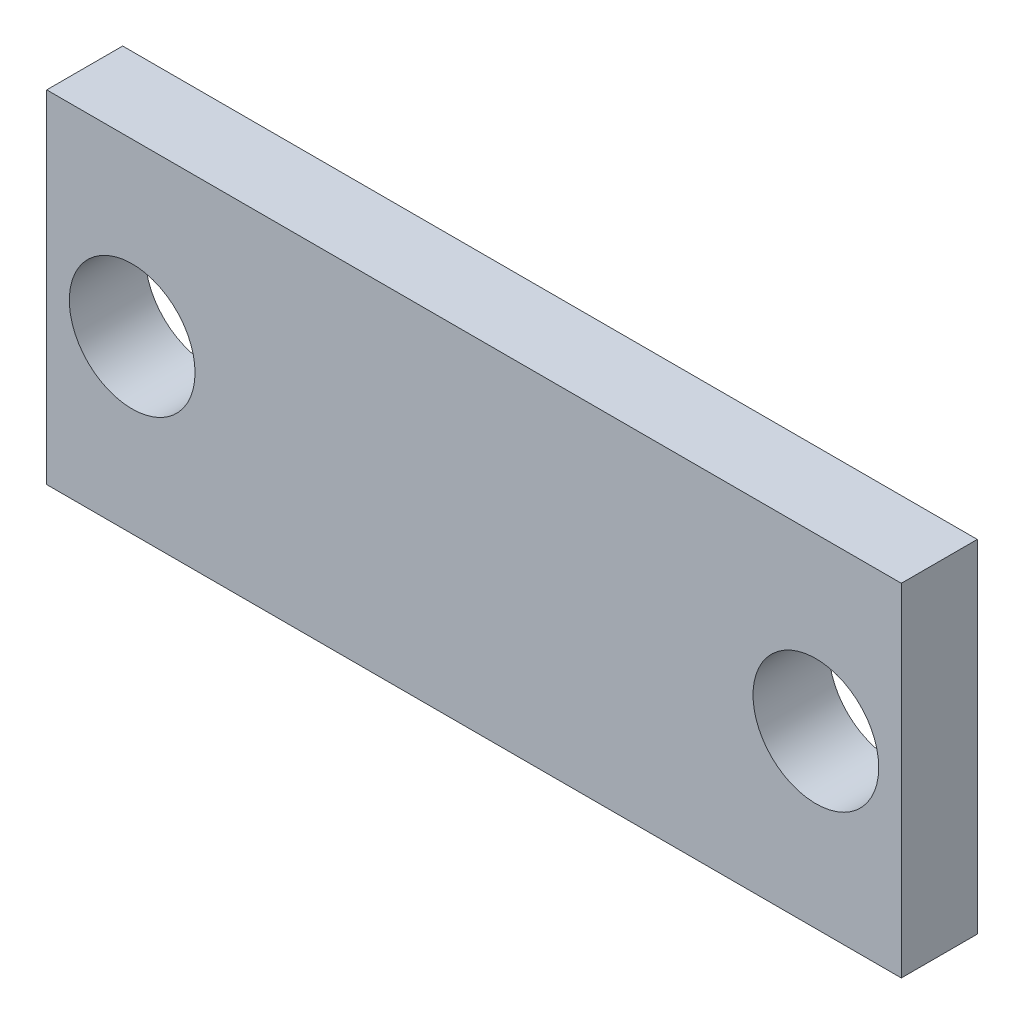
SolidWorks part; units mm, degrees
ref_plane "Front Plane" through (0, 0, 0) normal (0, 0, 1) x (1, 0, 0)
ref_plane "Top Plane" through (0, 0, 0) normal (0, 1, 0) x (1, 0, 0)
ref_plane "Right Plane" through (0, 0, 0) normal (1, 0, 0) x (0, 0, -1)
sketch "Sketch1" plane through (0, 0, 0) normal (0, 0, 1) x (1, 0, 0)
  line L1 (-10.6218, 14.6193) -> (11.8782, 14.6193)
  line L2 (-10.6218, 14.6193) -> (-10.6218, 5.6193)
  line L3 (-10.6218, 5.6193) -> (11.8782, 5.6193)
  line L4 (11.8782, 14.6193) -> (11.8782, 5.6193)
  circle A0 centre (-8.3718, 10.1227) radius 1.655
  circle A1 centre (9.6282, 10.1227) radius 1.655
  dimension "D3" = 2.25
  dimension "D4" = 3.31
  dimension "D1" = 22.5
  dimension "D2" = 9
  dimension "D5" = 2.25
extrude "Boss-Extrude1" add sketch "Sketch1" along normal blind 2
